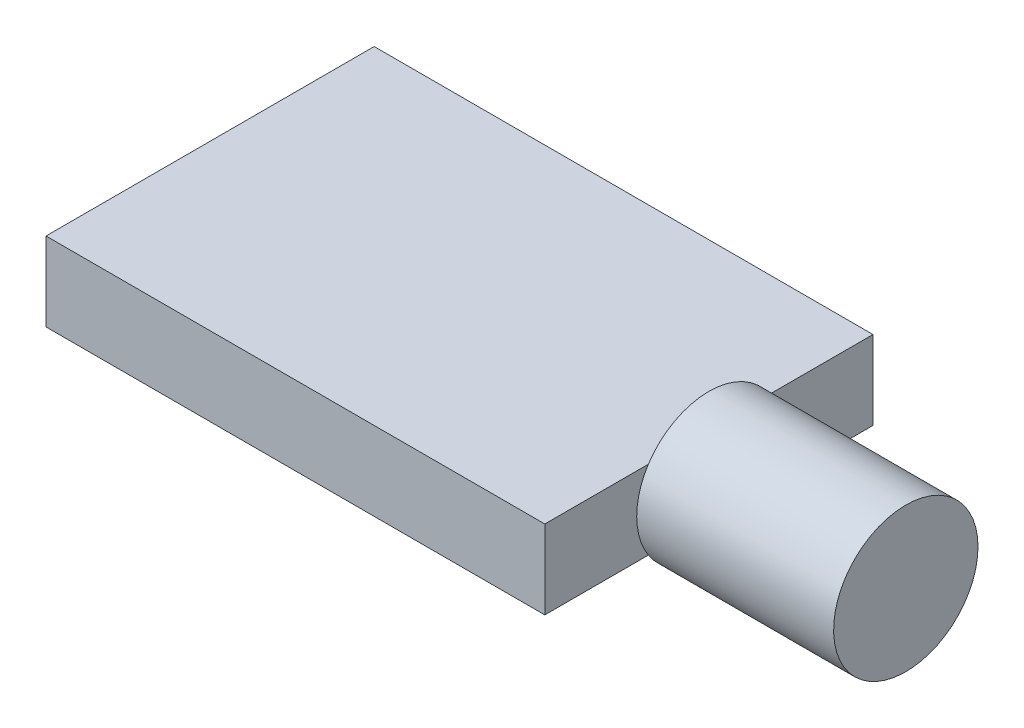
SolidWorks part; units mm, degrees
ref_plane "Front Plane" through (0, 0, 0) normal (0, 0, 1) x (1, 0, 0)
ref_plane "Top Plane" through (0, 0, 0) normal (0, 1, 0) x (1, 0, 0)
ref_plane "Right Plane" through (0, 0, 0) normal (1, 0, 0) x (0, 0, -1)
sketch "Sketch2" plane through (0, 0, 0) normal (0, 1, 0) x (1, 0, 0)
  line L1 (-19, -12.5) -> (19, -12.5)
  line L2 (-19, -12.5) -> (-19, 12.5)
  line L3 (-19, 12.5) -> (19, 12.5)
  line L4 (19, -12.5) -> (19, 12.5)
  line L5 (-19, -12.5) -> (19, 12.5) construction
  line L6 (-19, 12.5) -> (19, -12.5) construction
  point P0 (0, 0)
extrude "Boss-Extrude1" add sketch "Sketch2" along normal blind 6
sketch "Sketch3" plane through (19, 0, 0) normal (1, 0, 0) x (0, 0, -1)
  line L0 (0, -7.0395) -> (0, 20.6016) construction
  line L1 (-12.5, 3) -> (15.6885, 3) construction
  line L2 (-12.5, 6) -> (-12.5, 0) construction
  circle A0 centre (0, 3) radius 5.5
extrude "Boss-Extrude2" add sketch "Sketch3" along normal blind 15
